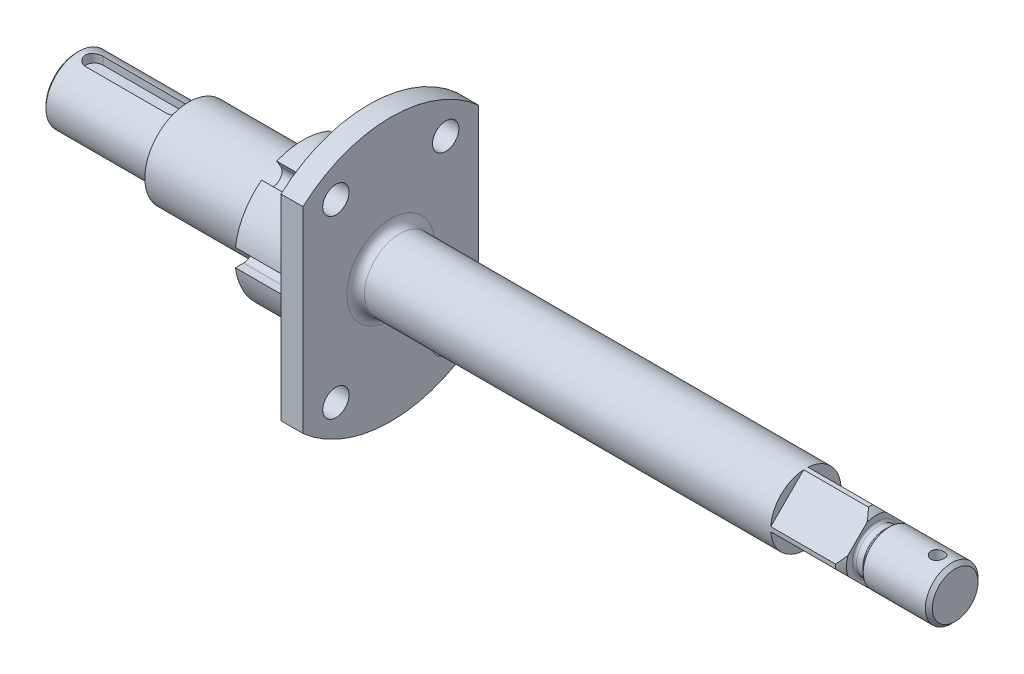
SolidWorks part; units mm, degrees
material "Сталь 20 ГОСТ 1050-2013"
ref_plane "Спереди" through (0, 0, 0) normal (0, 0, 1) x (1, 0, 0)
ref_plane "Сверху" through (0, 0, 0) normal (0, 1, 0) x (1, 0, 0)
ref_plane "Справа" through (0, 0, 0) normal (1, 0, 0) x (0, 0, -1)
sketch "Эскиз1" plane through (0, 0, 0) normal (0, 0, 1) x (1, 0, 0)
  line L0 (0, 0) -> (487.1574, 0) construction
  line L1 (129, 31) -> (103, 31)
  line L2 (103, 31) -> (103, 20)
  line L5 (0, 0) -> (0, 14)
  line L6 (1, 15) -> (51, 15)
  line L7 (51, 15) -> (51, 20)
  line L9 (51, 20) -> (103, 20)
  line L12 (133, 35) -> (133, 60)
  line L13 (133, 60) -> (143, 60)
  line L14 (143, 60) -> (143, 20)
  line L17 (147, 16) -> (361.5, 16)
  line L18 (364, 13.5) -> (364, 10.9)
  line L19 (365, 9.9) -> (367.7929, 9.9)
  line L20 (368.1464, 10.0464) -> (370.1, 12)
  line L21 (370.1, 12) -> (398.4, 12)
  line L22 (400, 10.4) -> (400, 0)
  line L23 (400, 0) -> (0, 0)
  line L25 (0, 14) -> (1, 15)
  line L26 (398.4, 12) -> (400, 10.4)
  line L27 (361.5, 16) -> (364, 13.5)
  arc A0 (143, 20) -> (147, 16) centre (147, 20) ccw
  arc A1 (129, 31) -> (133, 35) centre (129, 35) ccw
  arc A6 (367.7929, 9.9) -> (368.1464, 10.0464) centre (367.7929, 10.4) ccw
  arc A7 (364, 10.9) -> (365, 9.9) centre (365, 10.9) ccw
  point P8 (0, 15)
  point P20 (364, 16)
  point P24 (400, 12)
  point P46 (368, 9.9)
  point P49 (364, 9.9)
  dimension "D34" = 0.5
  dimension "D35" = 1
  dimension "D8" = 4
  dimension "D20" = 4
  dimension "D4" = 400
  dimension "D5" = 30
  dimension "D6" = 45
  dimension "D7" = 40
  dimension "D9" = 120
  dimension "D10" = 62
  dimension "D11" = 32
  dimension "D12" = 19.8
  dimension "D13" = 24
  dimension "D14" = 4
  dimension "D15" = 36
  dimension "D16" = 10
  dimension "D17" = 1
  dimension "D18" = 30
  dimension "D19" = 82
  dimension "D21" = 51
  dimension "D27" = 45
  dimension "D36" = 1.6
  dimension "D37" = 45
  dimension "D38" = 2.5
  dimension "D39" = 45
revolve "Повернуть1" add sketch "Эскиз1" angle 360 about L0
cosmetic thread "Условное изображение резьбы1" parameters "D2"=22.5
sketch "Эскиз2" plane through (400, 0, 0) normal (1, 0, 0) x (0, 0, -1)
  line L0 (0, -16.9706) -> (16.9706, 0)
  line L1 (0, -16.9706) -> (-16.9706, 0)
  line L2 (16.9706, 0) -> (0, 16.9706)
  line L3 (-16.9706, 0) -> (0, 16.9706)
  line L4 (0, -16.9706) -> (0, 16.9706) construction
  line L5 (16.9706, 0) -> (-16.9706, 0) construction
  point P1 (0, 0)
  dimension "D1" = 24
extrude "Вырез-Вытянуть1" cut sketch "Эскиз2" against normal blind 68 flip side to cut
ref_plane "Плоскость1" through (0, 15, 0) normal (0, 1, 0) x (1, 0, 0)
sketch "Эскиз3" plane through (0, 15, 0) normal (0, 1, 0) x (1, 0, 0)
  line L0 (8, 0) -> (45, 0) construction
  line L1 (8, 4) -> (45, 4)
  line L2 (8, -4) -> (45, -4)
  line L4 (51, 20) -> (51, -20) construction
  arc A0 (8, 4) -> (8, -4) centre (8, 0) ccw
  arc A1 (45, -4) -> (45, 4) centre (45, 0) ccw
  point P3 (26.5, 0)
  dimension "D1" = 8
  dimension "D2" = 45
  dimension "D3" = 2
extrude "Вырез-Вытянуть2" cut sketch "Эскиз3" against normal blind 4
sketch "Эскиз6" plane through (0, 0, 0) normal (0, 1, 0) x (1, 0, 0)
  line L0 (400, -10.4) -> (400, 10.4) construction
  circle A0 centre (392, 0) radius 3
  dimension "D1" = 6
  dimension "D2" = 8
extrude "Вырез-Вытянуть4" cut sketch "Эскиз6" against normal through all both and the other way through all
sketch "Эскиз7" plane through (143, 0, 0) normal (1, 0, 0) x (0, 0, -1)
  line L1 (-25, -40) -> (25, -40) construction
  line L2 (-25, -40) -> (-25, 40) construction
  line L3 (-25, 40) -> (25, 40) construction
  line L4 (25, -40) -> (25, 40) construction
  line L5 (-25, -40) -> (25, 40) construction
  line L6 (-25, 40) -> (25, -40) construction
  circle A0 centre (-25, 40) radius 6
  circle A1 centre (-25, -40) radius 6
  circle A2 centre (25, -40) radius 6
  circle A3 centre (25, 40) radius 6
  point P0 (0, 0)
  dimension "D1" = 12
  dimension "D2" = 50
  dimension "D3" = 80
extrude "Вырез-Вытянуть5" cut sketch "Эскиз7" against normal through all
sketch "Эскиз8" plane through (143, 0, 0) normal (1, 0, 0) x (0, 0, -1)
  line L1 (-40, -60) -> (40, -60)
  line L2 (-40, -60) -> (-40, 60)
  line L3 (-40, 60) -> (40, 60)
  line L4 (40, -60) -> (40, 60)
  line L5 (-40, -60) -> (40, 60) construction
  line L6 (-40, 60) -> (40, -60) construction
  circle A1 centre (0, 0) radius 60 construction
  point P0 (0, 0)
  point P7 (-40, 0)
  point P8 (40, 0)
  dimension "D1" = 80
extrude "Вырез-Вытянуть6" cut sketch "Эскиз8" against normal through all flip side to cut
sketch "Эскиз4" plane through (103, 0, 0) normal (-1, 0, 0) x (0, 0, 1)
  line L0 (0, 0) -> (35.2838, 0) construction
  line L1 (30.7409, 4) -> (27, 4)
  line L2 (27, -4) -> (30.7409, -4)
  arc A1 (30.7409, -4) -> (30.7409, 4) centre (0, 0) ccw
  arc A2 (27, 4) -> (27, -4) centre (27, 0) ccw
  circle A4 centre (0, 0) radius 31 construction
  dimension "D1" = 8
  dimension "D2" = 8
extrude "Вырез-Вытянуть3" cut sketch "Эскиз4" against normal blind 25
pattern_circular "Круговой массив1" count 6 over 360 about axis through (0, 0, 0) along (1, 0, 0) of "Вырез-Вытянуть3"
